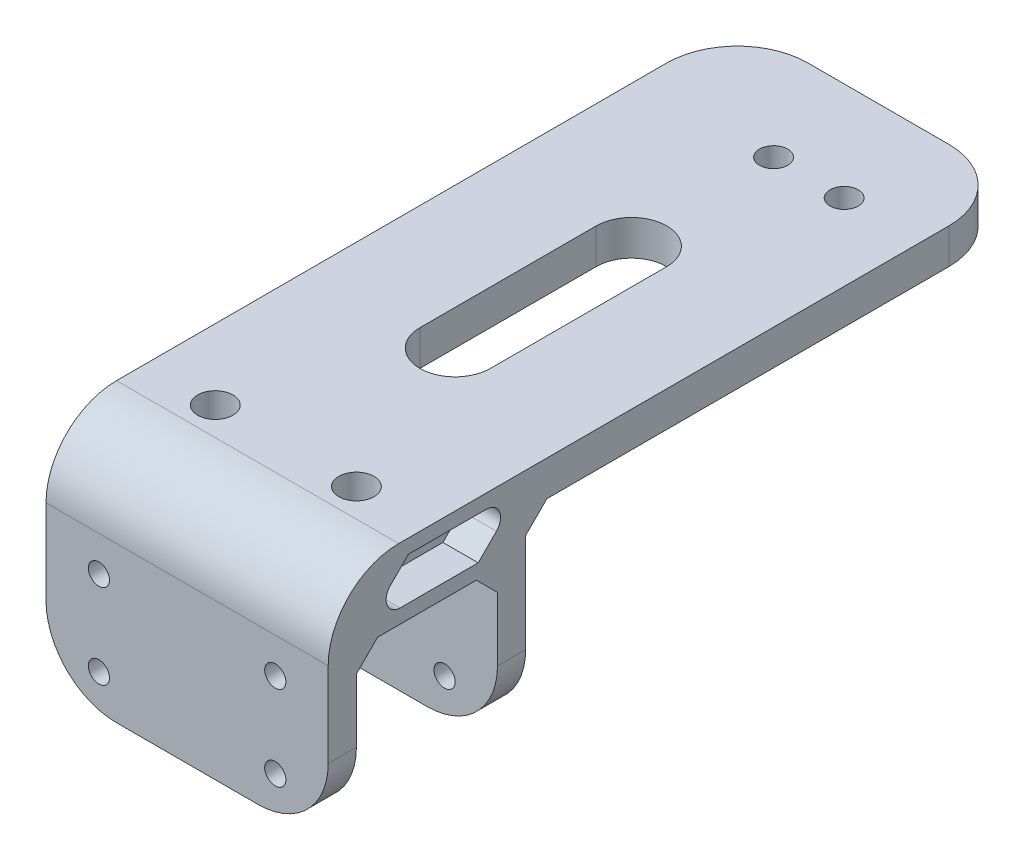
SolidWorks part; units mm, degrees
ref_plane "前视基准面" through (0, 0, 0) normal (0, 0, 1) x (1, 0, 0)
ref_plane "上视基准面" through (0, 0, 0) normal (0, 1, 0) x (1, 0, 0)
ref_plane "右视基准面" through (0, 0, 0) normal (1, 0, 0) x (0, 0, -1)
other "Configuration Table"
sketch "草图1" plane through (0, 0, 0) normal (0, 1, 0) x (1, 0, 0)
  line L1 (20, 14) -> (-20, 14)
  line L2 (20, 14) -> (20, -14)
  line L3 (20, -14) -> (-20, -14)
  line L4 (-20, 14) -> (-20, -14)
  line L5 (20, 14) -> (-20, -14) construction
  line L6 (20, -14) -> (-20, 14) construction
  point P0 (0, 0)
  dimension "D1" = 28
  dimension "D2" = 40
extrude "凸台-拉伸1" add sketch "草图1" along normal blind 10
sketch "草图2" plane through (0, 0, 0) normal (0, -1, 0) x (1, 0, 0)
  line L0 (20, 14) -> (20, -14) construction
  line L1 (-20, 14) -> (20, 14)
  line L2 (-20, 14) -> (-20, 10)
  line L3 (-20, 10) -> (20, 10)
  line L4 (20, 14) -> (20, 10)
  line L5 (-20, -14) -> (-20, 14) construction
  line L6 (-20, -10) -> (20, -10)
  line L7 (-20, -10) -> (-20, -14)
  line L8 (-20, -14) -> (20, -14)
  line L9 (20, -10) -> (20, -14)
  dimension "D1" = 4
  dimension "D2" = 4
extrude "凸台-拉伸2" add sketch "草图2" along normal blind 10
sketch "草图4" plane through (0, 0, -14) normal (0, 0, -1) x (-1, 0, 0)
  line L1 (20, 10) -> (20, -10) construction
  line L2 (-20, 10) -> (20, 10)
  line L3 (-20, 10) -> (-20, 5)
  line L4 (-20, 5) -> (20, 5)
  line L5 (20, 10) -> (20, 5)
  dimension "D1" = 5
extrude "凸台-拉伸3" add sketch "草图4" along normal blind 15
sketch "草图6" plane through (0, 0, -29) normal (0, 0, -1) x (-1, 0, 0)
  line L4 (-20, 10) -> (-20, 5)
  line L5 (-20, 5) -> (20, 5)
  line L6 (20, 5) -> (20, 10)
  line L7 (20, 10) -> (-20, 10)
  line L8 (-20, 10) -> (-20, 5)
  line L9 (-20, 5) -> (20, 5)
  line L10 (20, 5) -> (20, 10)
  line L11 (20, 10) -> (-20, 10)
  dimension "D1" = 0
extrude "凸台-拉伸4" add sketch "草图6" along normal blind 15
sketch "草图8" plane through (0, 10, 0) normal (0, 1, 0) x (1, 0, 0)
  line L0 (-20, -14) -> (20, -14) construction
  line L1 (20, -14) -> (20, 44) construction
  line L2 (-20, 44) -> (-20, -14) construction
  circle A0 centre (-10, 0) radius 2.5
  circle A1 centre (10, 0) radius 2.5
  dimension "D1" = 5
  dimension "D3" = 14
  dimension "D4" = 10
  dimension "D5" = 10
  dimension "D2" = 14
extrude "切除-拉伸2" cut sketch "草图8" against normal blind 15
chamfer "倒角1" distance 3 angle 45 2 edges at (0, 0, 10) (0, 0, -10)
fillet "圆角1" radius 10 1 edges at (0, 10, 14)
chamfer "倒角2" distance 3 angle 45 1 edges at (0, 5, -14)
sketch "草图9" plane through (0, 0, -14) normal (0, 0, -1) x (-1, 0, 0)
  line L0 (20, -10) -> (-20, -10) construction
  line L1 (20, 2) -> (20, -10) construction
  line L2 (-20, 2) -> (-20, -10) construction
  circle A0 centre (-12.5, -5) radius 1.5
  circle A1 centre (12.5, -5) radius 1.5
  dimension "D1" = 5
  dimension "D2" = 5
  dimension "D3" = 7.5
  dimension "D4" = 7.5
  dimension "D5" = 3
extrude "切除-拉伸3" cut sketch "草图9" against normal through all
sketch "草图10" plane through (20, 0, 0) normal (1, 0, 0) x (0, 0, -1)
  line L0 (-2.6185, 8) -> (-8.6185, 2)
  line L1 (-8.6185, 2) -> (7.2641, 2)
  line L2 (7.2641, 2) -> (13.2641, 8)
  line L3 (13.2641, 8) -> (-2.6185, 8)
  line L4 (-7, 0) -> (7, 0) construction
  line L5 (-4, 10) -> (44, 10) construction
  line L6 (-10, -3) -> (-7, 0) construction
  dimension "D1" = 2
  dimension "D2" = 2
extrude "切除-拉伸4" cut sketch "草图10" against normal blind 5
fillet "圆角3" radius 2 2 edges at (17.5, 8, -13.2641) (17.5, 2, 8.6185)
ref_plane "基准面1" through (0, 0, 0) normal (1, 0, 0) x (0, 0, -1)
mirror "镜向1" about plane through (0, 0, 0) normal (1, 0, 0) of "切除-拉伸4"
sketch "草图11" plane through (0, -10, 0) normal (0, -1, 0) x (1, 0, 0)
  line L0 (20, 14) -> (-20, 14) construction
  line L1 (-20, -14) -> (20, -14)
  line L2 (-20, -14) -> (-20, -7)
  line L3 (-20, -7) -> (20, -7)
  line L4 (20, -14) -> (20, -7)
  line L5 (-20, 14) -> (20, 14)
  line L6 (-20, 14) -> (-20, 7)
  line L7 (-20, 7) -> (20, 7)
  line L8 (20, 14) -> (20, 7)
  dimension "D1" = 7
  dimension "D2" = 7
extrude "凸台-拉伸5" add sketch "草图11" against normal blind 3 contours L2 L1 L4 L3 | L6 L5 L8 L7
chamfer "倒角3" distance 1 angle 45 2 edges at (0, -7, -7) (0, -7, 7)
sketch "草图12" plane through (0, 0, -44) normal (0, 0, -1) x (-1, 0, 0)
  line L1 (-20, 10) -> (20, 10)
  line L2 (-20, 10) -> (-20, 5)
  line L3 (-20, 5) -> (20, 5)
  line L4 (20, 10) -> (20, 5)
extrude "凸台-拉伸6" add sketch "草图12" along normal blind 30
sketch "草图13" plane through (0, 10, 0) normal (0, 1, 0) x (1, 0, 0)
  line L0 (20, -4) -> (20, 74) construction
  line L1 (-20, 74) -> (20, 74) construction
  circle A0 centre (9.14, 70) radius 2
  circle A1 centre (-0.86, 70) radius 2
  dimension "D1" = 4
  dimension "D2" = 10.86
  dimension "D3" = 10
  dimension "D4" = 4
  dimension "D5" = 4
extrude "切除-拉伸5" cut sketch "草图13" against normal blind 30
sketch "草图16" plane through (20, 0, 0) normal (1, 0, 0) x (0, 0, -1)
  line L1 (-10, -7) -> (10, -7)
  line L2 (-10, -7) -> (-10, -13.3861)
  line L3 (-10, -13.3861) -> (10, -13.3861)
  line L4 (10, -7) -> (10, -13.3861)
extrude "切除-拉伸6" cut sketch "草图16" against normal through all
sketch "草图17" plane through (0, -10, 0) normal (0, -1, 0) x (1, 0, 0)
  line L1 (-20, -10) -> (20, -10)
  line L2 (-20, -10) -> (-20, -14)
  line L3 (-20, -14) -> (20, -14)
  line L4 (20, -10) -> (20, -14)
  line L5 (-20, 14) -> (20, 14)
  line L6 (-20, 14) -> (-20, 10)
  line L7 (-20, 10) -> (20, 10)
  line L8 (20, 14) -> (20, 10)
extrude "凸台-拉伸8" add sketch "草图17" along normal blind 12
sketch "草图18" plane through (0, 0, 14) normal (0, 0, 1) x (1, 0, 0)
  line L0 (-20, -11) -> (20, -11) construction
  line L1 (-20, 0) -> (-20, -22) construction
  line L2 (20, 0) -> (20, -22) construction
  circle A0 centre (12.5, -5) radius 1.5 construction
  circle A1 centre (12.5, -5) radius 1.5
  circle A2 centre (-12.5, -5) radius 1.5 construction
  circle A3 centre (-12.5, -5) radius 1.5
  circle A4 centre (-12.5, -17) radius 1.5
  circle A5 centre (12.5, -17) radius 1.5
extrude "切除-拉伸7" cut sketch "草图18" against normal through all
sketch "草图19" plane through (0, 10, 0) normal (0, 1, 0) x (1, 0, 0)
  line L0 (0, 0) -> (0, 52.5874)
  line L1 (0, 49) -> (0, 24) construction
  line L2 (5, 49) -> (5, 24)
  line L3 (-5, 49) -> (-5, 24)
  line L4 (-20, 74) -> (20, 74) construction
  arc A0 (5, 49) -> (-5, 49) centre (0, 49) ccw
  arc A1 (-5, 24) -> (5, 24) centre (0, 24) ccw
  point P5 (0, 36.5)
  dimension "D3" = 25
  dimension "D1" = 10
  dimension "D2" = 25
extrude "切除-拉伸8" cut sketch "草图19" against normal through all
sketch "草图21" plane through (0, 0, -74) normal (0, 0, -1) x (-1, 0, 0)
  line L4 (-20, 10) -> (-20, 5)
  line L5 (-20, 5) -> (20, 5)
  line L6 (20, 5) -> (20, 10)
  line L7 (20, 10) -> (-20, 10)
  line L8 (-20, 10) -> (-20, 5)
  line L9 (-20, 5) -> (20, 5)
  line L10 (20, 5) -> (20, 10)
  line L11 (20, 10) -> (-20, 10)
  dimension "D1" = 0
extrude "凸台-拉伸9" add sketch "草图21" along normal blind 10
fillet "圆角5" radius 10 6 edges at (-20, -22, 12) (20, -22, 12) (20, -22, -12) (-20, -22, -12) (20, 7.5, -84) (-20, 7.5, -84)
